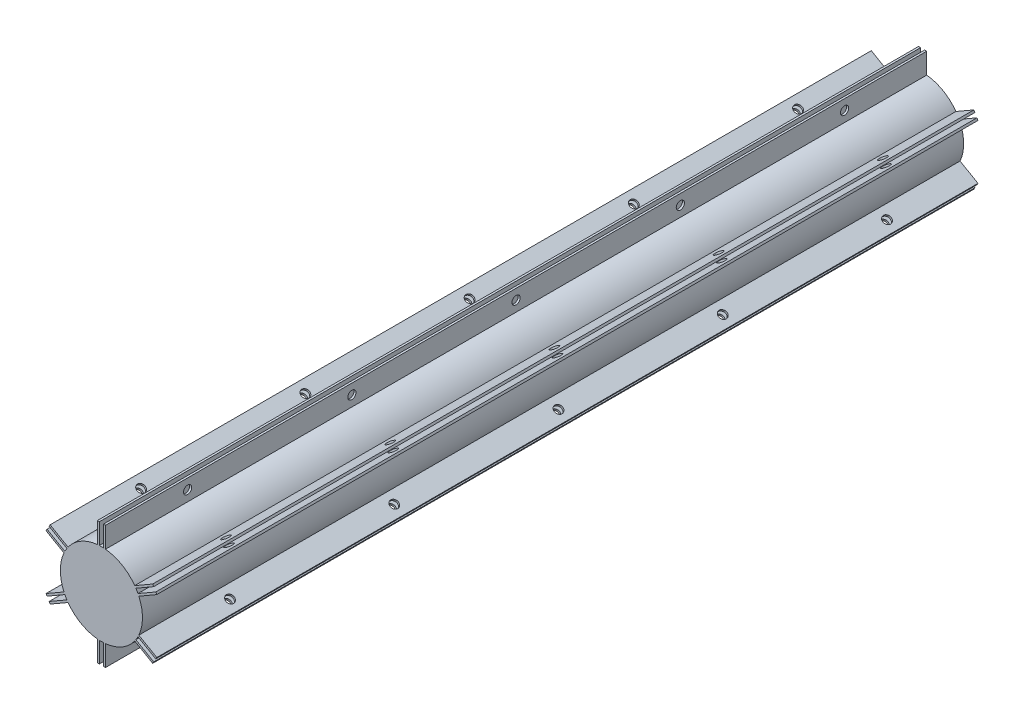
SolidWorks part; units mm, degrees
ref_plane "Front Plane" through (0, 0, 0) normal (0, 0, 1) x (1, 0, 0)
ref_plane "Top Plane" through (0, 0, 0) normal (0, 1, 0) x (1, 0, 0)
ref_plane "Right Plane" through (0, 0, 0) normal (1, 0, 0) x (0, 0, -1)
sketch "Sketch1" plane through (0, 0, 0) normal (0, 0, 1) x (1, 0, 0)
  circle A0 centre (0, 0) radius 10
  dimension "D2" = 20
extrude "Boss-Extrude1" add sketch "Sketch1" along normal mid plane 200
sketch "Sketch4" plane through (0, 0, 100) normal (0, 0, 1) x (1, 0, 0)
  line L0 (11, 0) -> (-11, 0) construction
  line L2 (-1, 0) -> (-0.5, 0)
  line L3 (0, 0) -> (0, 15.8331) construction
  line L4 (-1, 0) -> (-1, 15)
  line L5 (-1, 15) -> (-0.5, 15)
  line L6 (-0.5, 0) -> (-0.5, 15)
  line L7 (0, -14.2082) -> (0, 14.2082) construction
  line L8 (1, 15) -> (0.5, 15)
  line L9 (0.5, 0) -> (0.5, 15)
  line L10 (1, 0) -> (0.5, 0)
  line L11 (1, 0) -> (1, 15)
  dimension "D1" = 15
  dimension "D2" = 0.5
  dimension "D3" = 0.5
extrude "Boss-Extrude3" add sketch "Sketch4" against normal up to surface (200 mm away) up to face at (10, 0, -100)
pattern_circular "CirPattern7" count 6 over 360 about axis through (0, 0, 0) along (0, 0, 1) of "Boss-Extrude3"
sketch "Sketch7" plane through (-1, 0, 0) normal (-1, 0, 0) x (0, 0, 1)
  line L0 (-100, 15) -> (100, 15) construction
  line L1 (-100, 9.9499) -> (-100, 15) construction
  circle A0 centre (-80, 12.5) radius 1
  circle A1 centre (-40, 12.5) radius 1
  circle A2 centre (0, 12.5) radius 1
  circle A3 centre (40, 12.5) radius 1
  circle A4 centre (80, 12.5) radius 1
  dimension "D1" = 2
  dimension "D2" = 2.5
  dimension "D3" = 20
  dimension "D4" = 5
extrude "Cut-Extrude2" cut sketch "Sketch7" against normal blind 5
pattern_circular "CirPattern9" count 6 over 360 about axis through (0, 0, 100) along (0, 0, 1) of "Cut-Extrude2"
equation "\"drumDiameter\" = 20mm"
equation "\"D2@Sketch1\"=\"drumDiameter\""
equation "\"drumLength\"= 200mm"
equation "\"D1@Sketch4\"=\"drumDiameter\"*(0.5+\"drumAbove\")"
equation "\"foamThickness\"= 1mm"
equation "\"D3@Sketch4\"=\"foamThickness\"/2"
equation "\"drumAbove\"= 0.25"
equation "\"D2@Sketch7\"=\"drumDiameter\"*\"drumAbove\"/2"
